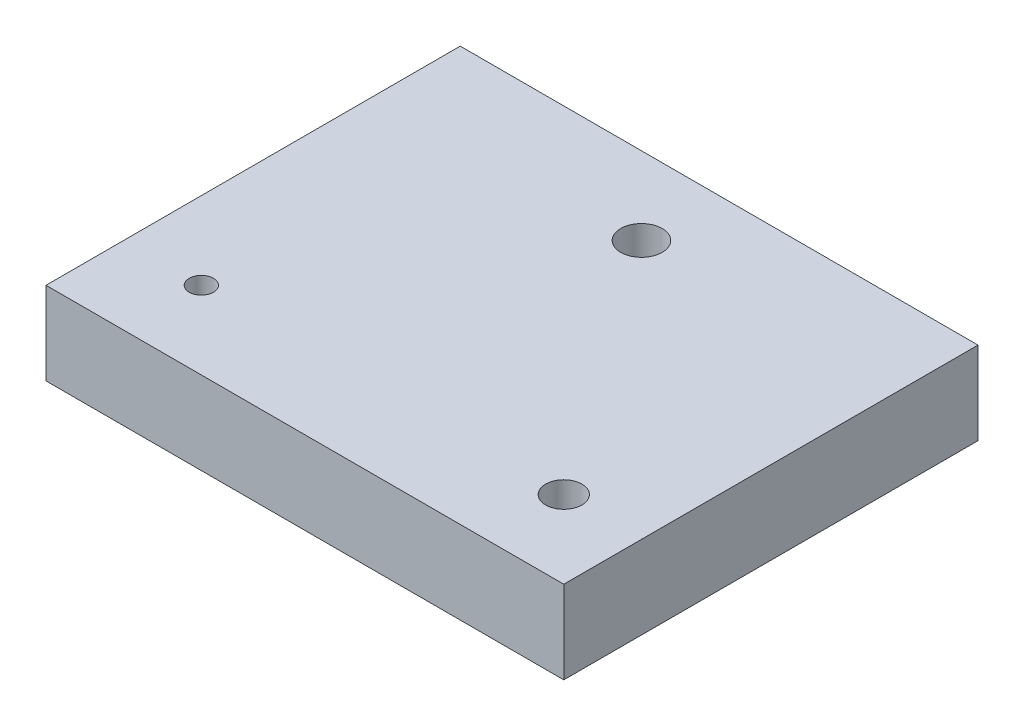
SolidWorks part; units mm, degrees
ref_plane "Front Plane" through (0, 0, 0) normal (0, 0, 1) x (1, 0, 0)
ref_plane "Top Plane" through (0, 0, 0) normal (0, 1, 0) x (1, 0, 0)
ref_plane "Right Plane" through (0, 0, 0) normal (1, 0, 0) x (0, 0, -1)
other "Configuration Table"
sketch "草图1" plane through (0, 0, 0) normal (0, 1, 0) x (1, 0, 0)
  line L0 (0, -8.8) -> (0, 8.8) construction
  line L1 (-50, -40) -> (50, -40)
  line L2 (-50, -40) -> (-50, 40)
  line L3 (-50, 40) -> (50, 40)
  line L4 (50, -40) -> (50, 40)
  line L5 (-50, -40) -> (50, 40) construction
  line L6 (-50, 40) -> (50, -40) construction
  circle A0 centre (-35, -25) radius 2.3426
  circle A1 centre (35, -25) radius 3.5
  circle A2 centre (0, 25) radius 4
  point P0 (0, 0)
extrude "凸台-拉伸1" add sketch "草图1" along normal blind 16
